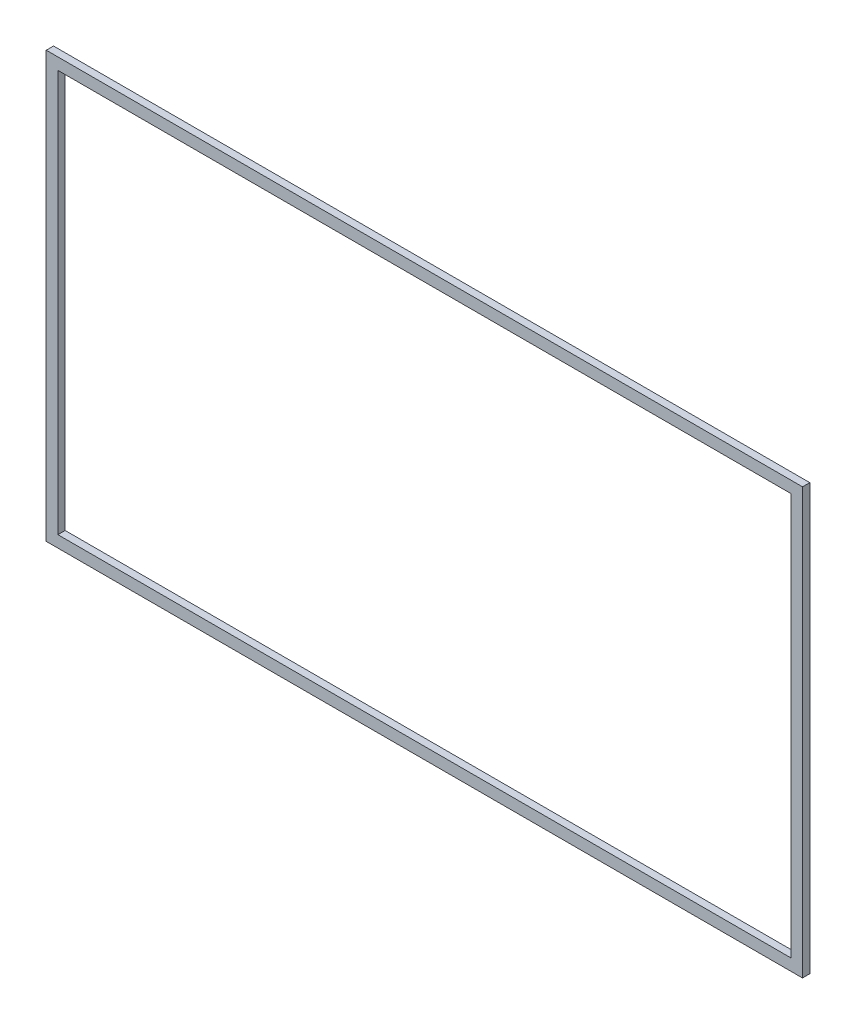
SolidWorks part; units mm, degrees
material "橡胶"
ref_plane "前视基准面" through (0, 0, 0) normal (0, 0, 1) x (1, 0, 0)
ref_plane "上视基准面" through (0, 0, 0) normal (0, 1, 0) x (1, 0, 0)
ref_plane "右视基准面" through (0, 0, 0) normal (1, 0, 0) x (0, 0, -1)
other "Configuration Table"
sketch "草图1" plane through (0, 0, 0) normal (0, 0, 1) x (1, 0, 0)
  line L1 (-25.2, -13.825) -> (25.2, -13.825)
  line L2 (-25.2, -13.825) -> (-25.2, 13.825)
  line L3 (-25.2, 13.825) -> (25.2, 13.825)
  line L4 (25.2, -13.825) -> (25.2, 13.825)
  line L5 (-25.2, -13.825) -> (25.2, 13.825) construction
  line L6 (-25.2, 13.825) -> (25.2, -13.825) construction
  line L7 (-26, -14.625) -> (26, -14.625)
  line L8 (-26, -14.625) -> (-26, 14.625)
  line L9 (-26, 14.625) -> (26, 14.625)
  line L10 (26, -14.625) -> (26, 14.625)
  line L11 (-26, -14.625) -> (26, 14.625) construction
  line L12 (-26, 14.625) -> (26, -14.625) construction
  point P0 (0, 0)
  point P6 (0, 0)
  dimension "D1" = 52
  dimension "D2" = 50.4
  dimension "D3" = 29.25
  dimension "D4" = 27.65
extrude "凸台-拉伸1" add sketch "草图1" along normal blind 0.5
